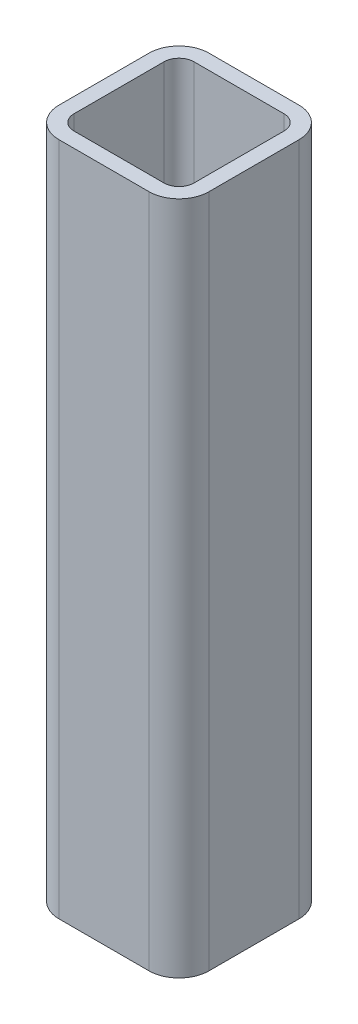
SolidWorks part; units mm, degrees
ref_plane "Front Plane" through (0, 0, 0) normal (0, 0, 1) x (1, 0, 0)
ref_plane "Top Plane" through (0, 0, 0) normal (0, 1, 0) x (1, 0, 0)
ref_plane "Right Plane" through (0, 0, 0) normal (1, 0, 0) x (0, 0, -1)
sketch3d "3DSketch1"
  line L0 (0, 0, 0) -> (0, 90, 0)
  dimension "D1" = 90
other "Square tube 20 X 20 X 2(1)"
ref_plane "Plane1" through (0, 0, 0) normal (0, 1, 0) x (1, 0, 0)
sketch "Sketch12" plane through (0, 0, 0) normal (0, 1, 0) x (1, 0, 0)
  line L0 (-6, -8) -> (6, -8)
  line L1 (-8, -6) -> (-8, 6)
  line L2 (6, 8) -> (-6, 8)
  line L3 (8, 6) -> (8, -6)
  line L4 (-6, -10) -> (6, -10)
  line L5 (-10, -6) -> (-10, 6)
  line L6 (6, 10) -> (-6, 10)
  line L7 (10, 6) -> (10, -6)
  arc A0 (10, 6) -> (6, 10) centre (6, 6) ccw
  arc A1 (6, -10) -> (10, -6) centre (6, -6) ccw
  arc A2 (-10, -6) -> (-6, -10) centre (-6, -6) ccw
  arc A3 (-6, 10) -> (-10, 6) centre (-6, 6) ccw
  arc A4 (-6, 8) -> (-8, 6) centre (-6, 6) ccw
  arc A5 (8, 6) -> (6, 8) centre (6, 6) ccw
  arc A6 (6, -8) -> (8, -6) centre (6, -6) ccw
  arc A7 (-8, -6) -> (-6, -8) centre (-6, -6) ccw
  point P0 (-10, 0)
  point P1 (10, 0)
  point P2 (0, 10)
  point P3 (0, -10)
  point P4 (0, 0)
  point P5 (-10, -10)
  point P6 (10, -10)
  point P7 (10, 10)
  point P8 (-10, 10)
  point P33 (0, 0)
  dimension "D1" = 4
  dimension "Thickness" = 2
  dimension "V_leg" = 20
